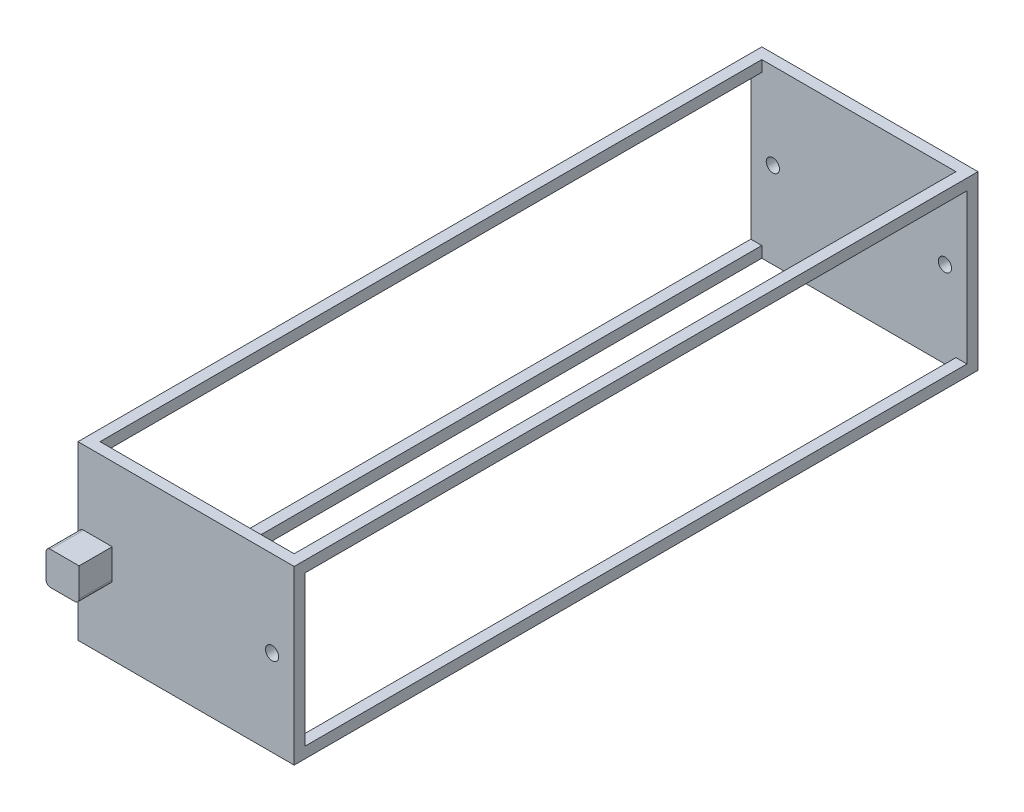
SolidWorks part; units mm, degrees
ref_plane "Front Plane" through (0, 0, 0) normal (0, 0, 1) x (1, 0, 0)
ref_plane "Top Plane" through (0, 0, 0) normal (0, 1, 0) x (1, 0, 0)
ref_plane "Right Plane" through (0, 0, 0) normal (1, 0, 0) x (0, 0, -1)
sketch "Sketch1" plane through (0, 0, 0) normal (0, 0, 1) x (1, 0, 0)
  line L0 (-20, 20) -> (-20, -370)
  line L5 (-20, -370) -> (470, -370)
  line L6 (470, 20) -> (470, -370)
  line L7 (-20, 20) -> (470, 20)
  dimension "D1" = 490
  dimension "D2" = 390
extrude "Boss-Extrude1" add sketch "Sketch1" along normal blind 25
sketch "Sketch2" plane through (0, 0, 25) normal (0, 0, 1) x (1, 0, 0)
  line L0 (225, 20) -> (225, -370) construction
  line L1 (-20, 20) -> (5, 20)
  line L2 (-20, 20) -> (-20, -5)
  line L3 (-20, -5) -> (5, -5)
  line L4 (5, 20) -> (5, -5)
  line L5 (470, 20) -> (-20, 20) construction
  line L6 (-20, -370) -> (470, -370) construction
  line L7 (-20, -175) -> (470, -175) construction
  line L8 (-20, 20) -> (-20, -370) construction
  line L9 (470, -370) -> (470, 20) construction
  line L10 (470, -5) -> (445, -5)
  line L11 (445, 20) -> (445, -5)
  line L12 (470, 20) -> (445, 20)
  line L13 (470, 20) -> (470, -5)
  line L14 (470, -370) -> (470, -345)
  line L15 (470, -370) -> (445, -370)
  line L16 (445, -370) -> (445, -345)
  line L17 (470, -345) -> (445, -345)
  line L18 (-20, -345) -> (5, -345)
  line L19 (5, -370) -> (5, -345)
  line L20 (-20, -370) -> (5, -370)
  line L21 (-20, -370) -> (-20, -345)
  dimension "D1" = 25
  dimension "25" = 25
extrude "Boss-Extrude2" add sketch "Sketch2" along normal blind 1500
sketch "Sketch3" plane through (0, 0, 1525) normal (0, 0, 1) x (1, 0, 0)
  line L1 (-20, 20) -> (470, 20)
  line L2 (-20, 20) -> (-20, -370)
  line L3 (-20, -370) -> (470, -370)
  line L4 (470, 20) -> (470, -370)
extrude "Boss-Extrude3" add sketch "Sketch3" along normal blind 25
sketch "Sketch4" plane through (0, 0, 1550) normal (0, 0, 1) x (1, 0, 0)
  line L0 (470, -370) -> (470, 20) construction
  line L1 (-20, 20) -> (-20, -370) construction
  line L2 (470, 20) -> (-20, 20) construction
  line L3 (-20, -370) -> (470, -370) construction
  circle A0 centre (420, -175) radius 15
  circle A1 centre (30, -175) radius 15
  dimension "D1" = 30
  dimension "30" = 30
  dimension "D2" = 50
  dimension "D3" = 50
  dimension "D4" = 195
  dimension "D5" = 195
extrude "Cut-Extrude1" cut sketch "Sketch4" against normal blind 1550 contours A0 | A1
sketch "Sketch5" plane through (0, 0, 1550) normal (0, 0, 1) x (1, 0, 0)
  circle A0 centre (30, -175) radius 13.709
extrude "Boss-Extrude4" add sketch "Sketch5" along normal blind 10 separate body
sketch "Sketch6" plane through (0, 0, 1560) normal (0, 0, 1) x (1, 0, 0)
  line L1 (-7.5, -137.5) -> (67.5, -137.5)
  line L2 (-7.5, -137.5) -> (-7.5, -212.5)
  line L3 (-7.5, -212.5) -> (67.5, -212.5)
  line L4 (67.5, -137.5) -> (67.5, -212.5)
  line L5 (-7.5, -137.5) -> (67.5, -212.5) construction
  line L6 (-7.5, -212.5) -> (67.5, -137.5) construction
  point P0 (30, -175)
  dimension "D1" = 75
  dimension "D2" = 75
extrude "Boss-Extrude5" add sketch "Sketch6" along normal blind 75
fillet "Fillet1" radius 10 3 edges at (67.5, -212.5, 1597.5) (-7.5, -212.5, 1597.5) (-7.5, -137.5, 1597.5)
